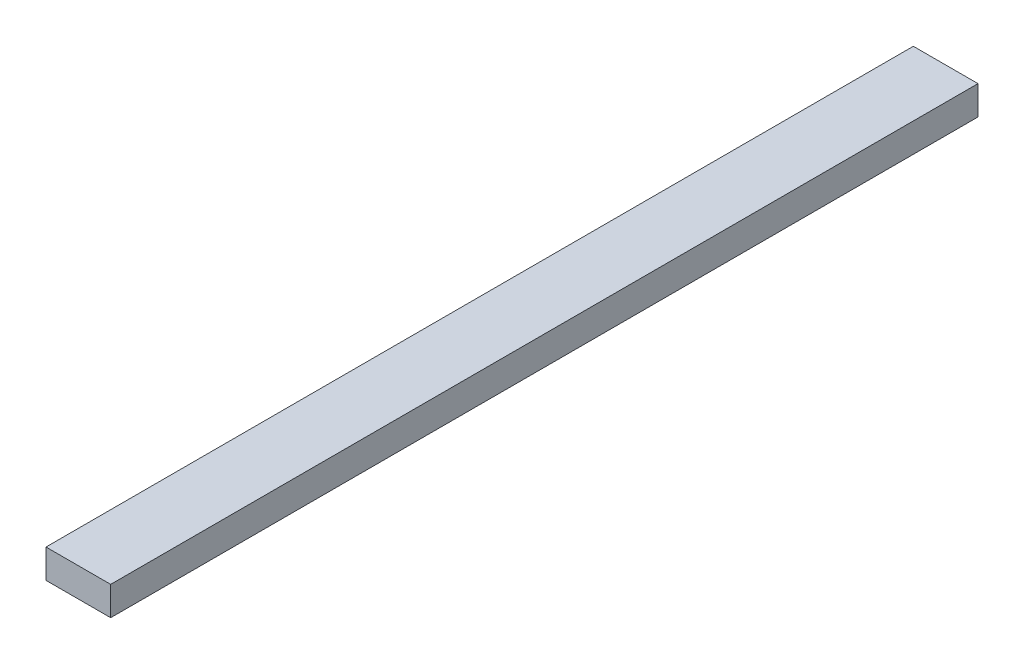
SolidWorks part; units mm, degrees
ref_plane "Front Plane" through (0, 0, 0) normal (1, 0, 0) x (0, 1, 0)
ref_plane "Top Plane" through (0, 0, 0) normal (0, 0, 1) x (0, 1, 0)
ref_plane "Right Plane" through (0, 0, 0) normal (0, 1, 0) x (-1, 0, 0)
sketch "Sketch1" plane through (0, 0, 0) normal (0, 0, 1) x (0, 1, 0)
  line L1 (-8.3312, -18.6436) -> (8.3312, -18.6436)
  line L2 (-8.3312, -18.6436) -> (-8.3312, 18.6436)
  line L3 (-8.3312, 18.6436) -> (8.3312, 18.6436)
  line L4 (8.3312, -18.6436) -> (8.3312, 18.6436)
  line L5 (-8.3312, -18.6436) -> (8.3312, 18.6436) construction
  line L6 (-8.3312, 18.6436) -> (8.3312, -18.6436) construction
  point P0 (0, 0)
  dimension "D1" = 16.6624
  dimension "D2" = 37.2872
extrude "Boss-Extrude1" add sketch "Sketch1" along normal mid plane 500
